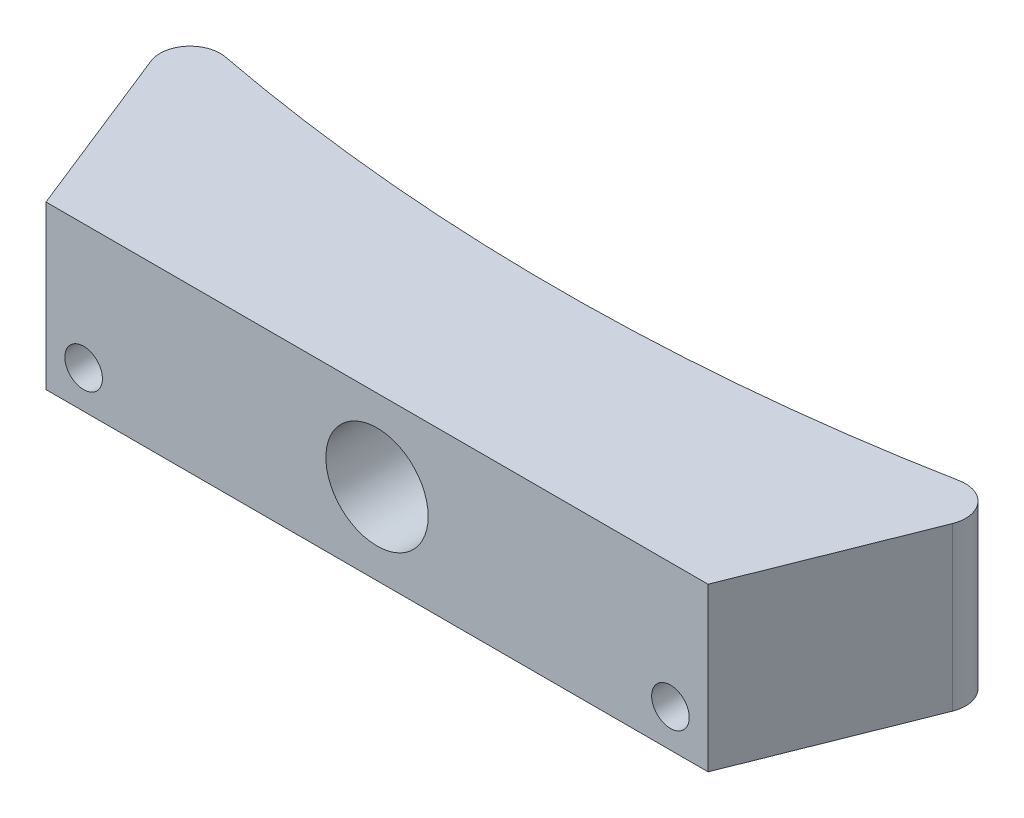
SolidWorks part; units mm, degrees
material "2A12"
ref_plane "前视基准面" through (0, 0, 0) normal (0, 0, 1) x (1, 0, 0)
ref_plane "上视基准面" through (0, 0, 0) normal (0, 1, 0) x (1, 0, 0)
ref_plane "右视基准面" through (0, 0, 0) normal (1, 0, 0) x (0, 0, -1)
sketch "草图1" plane through (0, 0, 0) normal (0, 0, 1) x (1, 0, 0)
  circle A0 centre (0, 0) radius 5.4
  dimension "D1" = 10.8
extrude "拉伸1" add sketch "草图1" along normal blind 45
sketch "草图2" plane through (0, 0, 45) normal (0, 0, 1) x (1, 0, 0)
  line L0 (0, 0) -> (0, -3.6) construction
  line L1 (-5, -3.6) -> (5, -3.6)
  line L2 (-5, -3.6) -> (-5, -5.6)
  line L3 (-5, -5.6) -> (5, -5.6)
  line L4 (5, -3.6) -> (5, -5.6)
  dimension "D1" = 3.6
  dimension "D2" = 10
  dimension "D3" = 2
extrude "拉伸2" [suppressed] cut sketch "草图2" against normal up to surface (40 mm away)
sketch "草图4" plane through (0, 0, 0) normal (0, -1, 0) x (1, 0, 0)
  line L0 (-22, 0) -> (22, 0)
  line L1 (-22, 0) -> (-28, -15.0512)
  line L4 (28, -15.0512) -> (22, 0)
  line L5 (0, 0) -> (0, -12) construction
  arc A0 (-28, -15.0512) -> (28, -15.0512) centre (0, -142) cw
  dimension "D3" = 130
  dimension "D1" = 44
  dimension "D2" = 12
  dimension "D4" = 56
extrude "拉伸3" add sketch "草图4" against normal mid plane 10.8
hole_wizard "M8x1.0 Tapped Hole1" positions "3D草图1" profile "草图5" tap size "M8x1.0" standard "GB"
sketch3d "3D草图1"
  line L0 (0, 0, 45) -> (0, 0, 0) construction
  point P0 (0, 0, 45)
sketch "草图5" plane through (0, 0, 45) normal (1, 0, 0) x (0, -1, 0)
  line L0 (0, 0) -> (0, 15.103)
  line L1 (0, 15.103) -> (3.5, 13)
  line L2 (3.5, 13) -> (3.5, 0)
  line L5 (3.5, 0) -> (0, 0)
  line L10 (0, 15.103) -> (-3.5, 13) construction
  line L11 (0, -6.35) -> (0, 107.95) construction
  dimension "螺纹孔钻头直径" = 7
  dimension "螺纹孔钻头深度" = 13
  dimension "导头角度" = 118
cosmetic thread "孔螺蚊线1" parameters "D1"=10, "D2"=8
sketch "草图6" plane through (0, 0, 0) normal (0, 0, 1) x (1, 0, 0)
  line L0 (-19.5, -2.9) -> (19.5, -2.9)
  line L1 (0, 0) -> (0, -2.9)
  line L3 (22, -5.4) -> (0, -5.4) construction
  dimension "D1" = 2.5
  dimension "D2" = 39
hole_wizard "M3 Tapped Hole1" positions "3D草图2" profile "草图7" tap size "M3" standard "GB"
sketch3d "3D草图2"
  point P0 (-19.5, -2.9, 0)
  point P3 (19.5, -2.9, 0)
sketch "草图7" plane through (-19.5, -2.9, 0) normal (1, 0, 0) x (0, -1, 0)
  line L0 (0, 0) -> (0, 8.2511)
  line L1 (0, 8.2511) -> (1.25, 7.5)
  line L2 (1.25, 7.5) -> (1.25, 0)
  line L5 (1.25, 0) -> (0, 0)
  line L10 (0, 8.2511) -> (-1.25, 7.5) construction
  line L11 (0, -6.35) -> (0, 107.95) construction
  dimension "螺纹孔钻头直径" = 2.5
  dimension "螺纹孔钻头深度" = 7.5
  dimension "导头角度" = 118
cosmetic thread "孔螺蚊线2" parameters "D1"=6, "D2"=3
cosmetic thread "孔螺蚊线3" parameters "D1"=6, "D2"=3
chamfer "倒角2" distance 0.5 angle 45 1 edges at (5.4, 0, 45)
sketch "草图9" plane through (0, 0, 45) normal (0, 0, 1) x (1, 0, 0)
  circle A0 centre (0, 0) radius 4.25
  dimension "D1" = 8.5
extrude "拉伸5" cut sketch "草图9" against normal blind 2
chamfer "倒角3" distance 0.5 angle 45 2 edges at (4.25, 0, 45) (3.5, 0, 43)
sketch "草图10" plane through (0, 0, 0) normal (0, 0, 1) x (1, 0, 0)
  circle A0 centre (0, 0) radius 6.9354
extrude "切除-拉伸1" cut sketch "草图10" along normal blind 86
hole_wizard "M8 螺纹孔1" positions "草图12" profile "草图11" tap size "M8" standard "GB"
sketch "草图12" plane through (0, 0, 0) normal (0, 0, 1) x (1, 0, 0)
  point P0 (0, 0)
sketch "草图11" plane through (0, 0, 0) normal (1, 0, 0) x (0, -1, 0)
  line L0 (0, 0) -> (0, 11.0429)
  line L1 (0, 11.0429) -> (3.4, 9)
  line L2 (3.4, 9) -> (3.4, 0)
  line L5 (3.4, 0) -> (0, 0)
  line L10 (0, 11.0429) -> (-3.4, 9) construction
  line L11 (0, -6.35) -> (0, 107.95) construction
  dimension "螺纹孔钻头直径" = 6.8
  dimension "螺纹孔钻头深度" = 9
  dimension "导头角度" = 118
cosmetic thread "孔螺蚊线4" parameters "D1"=12.0445, "D2"=8
fillet "圆角1" radius 2 2 edges at (-28, 0, -15.0512) (28, 0, -15.0512)
